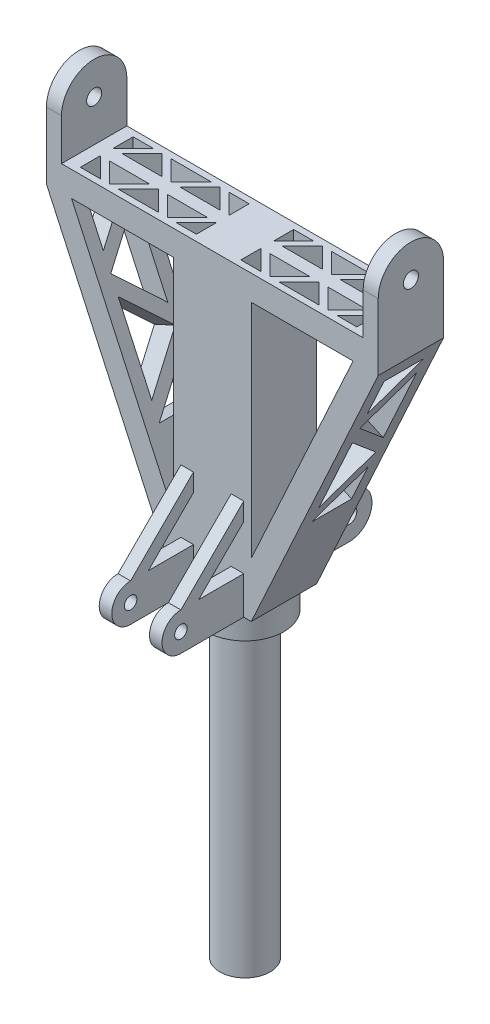
SolidWorks part; units mm, degrees
ref_plane "Front Plane" through (0, 0, 0) normal (0, 0, 1) x (1, 0, 0)
ref_plane "Top Plane" through (0, 0, 0) normal (0, 1, 0) x (1, 0, 0)
ref_plane "Right Plane" through (0, 0, 0) normal (1, 0, 0) x (0, 0, -1)
sketch "Sketch27" plane through (0, 0, 0) normal (0, 0, 1) x (1, 0, 0)
  line L0 (66, -50) -> (-66, -50)
  line L1 (-66, -50) -> (-66, 100)
  line L2 (-66, 100) -> (-60, 100)
  line L3 (-60, 100) -> (-60, 70)
  line L4 (-60, 70) -> (60, 70)
  line L5 (0, 0) -> (0, 82.1741) construction
  line L6 (60, 100) -> (60, 70)
  line L7 (66, 100) -> (60, 100)
  line L8 (66, -50) -> (66, 100)
  point P10 (0, 0)
  point P11 (0, 70)
  dimension "D1" = 120
  dimension "D2" = 6
  dimension "D3" = 150
  dimension "D4" = 30
extrude "Tykkelse leddfester og bredde/høyde selve modellen" add sketch "Sketch27" along normal mid plane 26
sketch "Sketch28" plane through (0, -50, 0) normal (0, -1, 0) x (1, 0, 0)
  line L0 (-66, -13) -> (66, -13) construction
  line L1 (66, 13) -> (66, -13) construction
  circle A1 centre (0, 0) radius 10.5
  circle A2 centre (0, 0) radius 15.5
  point P6 (0, -13)
  point P9 (66, 0)
  dimension "D1" = 21
  dimension "D2" = 5
extrude "Hull til lårben/karbonfiberrør" add sketch "Sketch28" along normal blind 10
sketch "Sketch29" plane through (66, 0, 0) normal (1, 0, 0) x (0, 0, -1)
  line L0 (-13, 100) -> (13, 100) construction
  line L1 (-13, 86.5) -> (-13, 71.5)
  line L2 (13, 86.5) -> (13, 71.5)
  line L4 (-14, 101) -> (0, 101)
  line L8 (0, 86.5) -> (0, 83.5) construction
  line L9 (0, 100) -> (0, 99.5) construction
  line L13 (-13, 71.5) -> (-14, 71.5)
  line L14 (-14, 71.5) -> (-14, 101)
  line L18 (13, 71.5) -> (14, 71.5)
  line L19 (14, 71.5) -> (14, 101)
  line L20 (14, 101) -> (0, 101)
  circle A0 centre (0, 86.5) radius 3
  arc A1 (13, 86.5) -> (-13, 86.5) centre (0, 86.5) ccw
  circle A2 centre (0, 86.5) radius 13 construction
  point P4 (0, 100)
  point P14 (-7, 101)
  dimension "D1" = 6
  dimension "D3" = 15
  dimension "D4" = 0.5
  dimension "D5" = 1
  dimension "D6" = 1
  dimension "D2" = 10
extrude "Skruehull leddfester" cut sketch "Sketch29" against normal through all both and the other way through all
sketch "Fasong (mønster på selve kroppen)" plane through (0, 0, 13) normal (0, 0, 1) x (1, 0, 0)
  line L0 (-66, 60) -> (-15.5, -50)
  line L1 (-66, 86.5) -> (-66, -50) construction
  line L2 (-15.5, -50) -> (-66, -50)
  line L3 (-66, -50) -> (-66, 60)
  line L4 (-60, 70) -> (-66, 70) construction
  line L5 (0, 0) -> (0, 49.2612) construction
  line L6 (15.5, -50) -> (66, -50)
  line L7 (66, 60) -> (15.5, -50)
  line L8 (66, -50) -> (66, 60)
  line L9 (-15.5, -50) -> (-15.5, 60) construction
  line L11 (15.5, -50) -> (15.5, 60) construction
  line L12 (-66, 60) -> (-56, 60) construction
  line L13 (-56, 60) -> (-15.5, -28.2178)
  line L14 (-56, 60) -> (-15.5, 60)
  line L15 (-15.5, 60) -> (-15.5, -28.2178)
  line L16 (56, 60) -> (15.5, 60)
  line L17 (56, 60) -> (15.5, -28.2178)
  line L18 (15.5, 60) -> (15.5, -28.2178)
  dimension "D1" = 10
  dimension "D2" = 10
  dimension "D3" = 31
sketch "Sketch33" plane through (0, 0, -13) normal (0, 0, -1) x (-1, 0, 0)
  line L4 (8.441, -50) -> (-8.441, -50) construction
  line L5 (-3.5, -30) -> (-3.5, -50)
  line L6 (-3.5, -50) -> (-8.5, -50)
  line L7 (-8.5, -50) -> (-8.5, -30)
  line L8 (-8.5, -30) -> (-3.5, -30)
  line L9 (0, 0) -> (0, 33.6157) construction
  line L10 (0, 0) -> (0, 49.2612) construction
  line L11 (8.5, -50) -> (8.5, -30)
  line L12 (3.5, -50) -> (8.5, -50)
  line L13 (3.5, -30) -> (3.5, -50)
  line L14 (8.5, -30) -> (3.5, -30)
  dimension "D1" = 5
  dimension "D2" = 20
  dimension "D3" = 7
extrude "Bredde og avstand stempelende" add sketch "Sketch33" along normal blind 60
sketch "Rod-ende, justere lengden (altså feste til største sylinder)" plane through (8.5, 0, 0) normal (1, 0, 0) x (0, 0, -1)
  line L0 (13, -30) -> (13, -50) construction
  line L5 (43, -51) -> (74, -51)
  line L6 (74, -51) -> (74, -29)
  line L7 (74, -29) -> (43, -29)
  line L9 (73, -50) -> (13, -50) construction
  line L11 (73, -30) -> (73, -50) construction
  line L12 (73, -30) -> (13, -30) construction
  line L13 (33, -49) -> (13, -49)
  line L14 (13, -50) -> (13, 86.5) construction
  line L15 (13, -49) -> (13, -51)
  line L16 (13, -51) -> (43, -51)
  line L17 (43, -29) -> (13, -29)
  line L18 (13, -29) -> (13, -31)
  line L19 (13, -31) -> (33, -31)
  circle A0 centre (33, -40) radius 3
  arc A1 (33, -49) -> (33, -31) centre (33, -40) ccw
  circle A2 centre (33, -40) radius 9 construction
  point P6 (13, -40)
  dimension "D1" = 6
  dimension "D3" = 20
  dimension "D4" = 1
  dimension "D5" = 1
  dimension "D6" = 1
  dimension "D2" = 6
sketch "Sketch39" plane through (0, 0, 13) normal (0, 0, 1) x (1, 0, 0)
  line L1 (-7.5, -50) -> (-7.5, -35)
  line L3 (-7.5, -35) -> (-12.5, -35)
  line L4 (-12.5, -35) -> (-12.5, -50)
  line L5 (-12.5, -50) -> (-7.5, -50)
  line L11 (0, 0) -> (0, 49.2612) construction
  line L12 (0, 0) -> (0, 21.5969) construction
  line L13 (12.5, -50) -> (7.5, -50)
  line L14 (12.5, -35) -> (12.5, -50)
  line L15 (7.5, -35) -> (12.5, -35)
  line L16 (7.5, -50) -> (7.5, -35)
  line L17 (-8.441, -50) -> (8.441, -50) construction
  dimension "D1" = 15
  dimension "D2" = 5
  dimension "D3" = 7.5
extrude "Cut-Extrude4" cut sketch "Fasong (mønster på selve kroppen)" against normal through all
sketch "Sketch40" plane through (-31.7606, -14.581, 0) normal (-0.9088, -0.4172, 0) x (0, 0, 1)
  line L0 (0, 82.065) -> (0, 35.3376) construction
  line L1 (-13, 82.065) -> (13, 82.065) construction
  line L2 (-8, 75.565) -> (8, 75.565)
  line L3 (-13, -38.9732) -> (-13, 82.065) construction
  line L4 (-8, 75.565) -> (8, 59.565)
  line L6 (-8, 68.4939) -> (8, 52.4939)
  line L8 (-8, 36.4939) -> (8, 52.4939)
  line L9 (8, 75.565) -> (8, 59.565)
  line L10 (-8, 36.4939) -> (-8, 68.4939)
  line L13 (8, 13.4229) -> (-8, 29.4229)
  line L16 (8, 45.4229) -> (-8, 29.4229)
  line L18 (8, 13.4229) -> (8, 45.4229)
  line L19 (-8, 22.3518) -> (8, 6.3518)
  line L20 (8, 6.3518) -> (-8, 6.3518)
  line L21 (-8, 6.3518) -> (-8, 22.3518)
  line L22 (-13, -38.9732) -> (0, -38.9732) construction
  point P8 (0, 75.565)
  dimension "D1" = 6.5
  dimension "D2" = 5
  dimension "D3" = 45
  dimension "D4" = 90
  dimension "D5" = 5
  dimension "D6" = 5
  dimension "D7" = 90
  dimension "D8" = 5
  dimension "D9" = 45.325
extrude "Sidemønster" cut sketch "Sketch40" against normal up to vertex (9.088 mm away)
sketch "Sketch42" plane through (31.7606, -14.581, 0) normal (0.9088, -0.4172, 0) x (0, 0, -1)
  line L3 (0, 82.065) -> (0, 75.565) construction
  line L4 (13, 82.065) -> (-13, 82.065) construction
  line L5 (8, 75.565) -> (-8, 75.565)
  line L6 (-13, 82.065) -> (-13, -38.9732) construction
  line L7 (-8, 75.565) -> (-8, 59.565)
  line L8 (-8, 59.565) -> (8, 75.565)
  line L9 (8, 68.4939) -> (-8, 52.4939)
  line L11 (8, 36.4939) -> (8, 68.4939)
  line L12 (8, 36.4939) -> (-8, 52.4939)
  line L13 (-8, 45.4229) -> (8, 29.4229)
  line L15 (-8, 13.4229) -> (-8, 45.4229)
  line L16 (-8, 13.4229) -> (8, 29.4229)
  line L17 (8, 22.3518) -> (-8, 6.3518)
  line L18 (-8, 6.3518) -> (8, 6.3518)
  line L19 (8, 6.3518) -> (8, 22.3518)
  point P8 (0, 82.065)
  point P11 (0, 75.565)
  dimension "D1" = 6.5
  dimension "D2" = 5
  dimension "D3" = 45
  dimension "D4" = 5
  dimension "D5" = 45
  dimension "D6" = 45
  dimension "D7" = 5
  dimension "D9" = 5
extrude "Sidemønster 2" cut sketch "Sketch42" against normal up to vertex (9.088 mm away)
sketch "Sketch44" plane through (0, -50, 0) normal (0, -1, 0) x (1, 0, 0)
  circle A0 centre (0, 0) radius 10.5
  dimension "D1" = 21
extrude "Utvidet lårbenhull inn i selve kroppen" cut sketch "Sketch44" against normal blind 40
sketch "Sketch45" plane through (0, 70, 0) normal (0, 1, 0) x (1, 0, 0)
  line L3 (-39.9289, 10.5) -> (-31.9289, 2.5)
  line L5 (-23.9289, 10.5) -> (-39.9289, 10.5)
  line L6 (-16.8579, 10.5) -> (-8.8579, 2.5)
  line L7 (0, 0) -> (0, 11.265) construction
  line L8 (0, 0) -> (-55, 0) construction
  line L9 (-60, -13) -> (-60, 13) construction
  line L10 (-55, 2.5) -> (-55, 10.5)
  line L11 (-55, 10.5) -> (-47, 10.5)
  line L12 (-47, 10.5) -> (-55, 2.5)
  line L13 (60, 13) -> (-60, 13) construction
  line L14 (-43.4645, 10.5) -> (-51.4645, 2.5)
  line L15 (-51.4645, 2.5) -> (-35.4645, 2.5)
  line L17 (-43.4645, 10.5) -> (-35.4645, 2.5)
  line L18 (-23.9289, 10.5) -> (-31.9289, 2.5)
  line L19 (-20.3934, 10.5) -> (-28.3934, 2.5)
  line L20 (-28.3934, 2.5) -> (-12.3934, 2.5)
  line L22 (-20.3934, 10.5) -> (-12.3934, 2.5)
  line L23 (-8.8579, 2.5) -> (-8.8579, 10.5)
  line L24 (-8.8579, 10.5) -> (-16.8579, 10.5)
  line L25 (-8.8579, -2.5) -> (-8.8579, -10.5)
  line L26 (-16.8579, -10.5) -> (-8.8579, -2.5)
  line L27 (-8.8579, -10.5) -> (-16.8579, -10.5)
  line L28 (-20.3934, -10.5) -> (-12.3934, -2.5)
  line L29 (-28.3934, -2.5) -> (-12.3934, -2.5)
  line L30 (-20.3934, -10.5) -> (-28.3934, -2.5)
  line L31 (-23.9289, -10.5) -> (-31.9289, -2.5)
  line L32 (-23.9289, -10.5) -> (-39.9289, -10.5)
  line L33 (-39.9289, -10.5) -> (-31.9289, -2.5)
  line L34 (-43.4645, -10.5) -> (-35.4645, -2.5)
  line L35 (-51.4645, -2.5) -> (-35.4645, -2.5)
  line L36 (-43.4645, -10.5) -> (-51.4645, -2.5)
  line L37 (-55, -10.5) -> (-47, -10.5)
  line L38 (-55, -2.5) -> (-55, -10.5)
  line L39 (-47, -10.5) -> (-55, -2.5)
  line L40 (8.8579, 2.5) -> (8.8579, 10.5)
  line L41 (16.8579, 10.5) -> (8.8579, 2.5)
  line L42 (8.8579, 10.5) -> (16.8579, 10.5)
  line L43 (16.8579, -10.5) -> (8.8579, -2.5)
  line L44 (8.8579, -10.5) -> (16.8579, -10.5)
  line L45 (8.8579, -2.5) -> (8.8579, -10.5)
  line L46 (20.3934, -10.5) -> (28.3934, -2.5)
  line L47 (28.3934, -2.5) -> (12.3934, -2.5)
  line L48 (20.3934, -10.5) -> (12.3934, -2.5)
  line L49 (20.3934, 10.5) -> (12.3934, 2.5)
  line L50 (28.3934, 2.5) -> (12.3934, 2.5)
  line L51 (20.3934, 10.5) -> (28.3934, 2.5)
  line L52 (23.9289, 10.5) -> (31.9289, 2.5)
  line L53 (23.9289, 10.5) -> (39.9289, 10.5)
  line L54 (39.9289, 10.5) -> (31.9289, 2.5)
  line L55 (23.9289, -10.5) -> (39.9289, -10.5)
  line L56 (39.9289, -10.5) -> (31.9289, -2.5)
  line L57 (23.9289, -10.5) -> (31.9289, -2.5)
  line L58 (43.4645, -10.5) -> (51.4645, -2.5)
  line L59 (51.4645, -2.5) -> (35.4645, -2.5)
  line L60 (43.4645, -10.5) -> (35.4645, -2.5)
  line L61 (55, -2.5) -> (55, -10.5)
  line L62 (47, -10.5) -> (55, -2.5)
  line L63 (55, -10.5) -> (47, -10.5)
  line L64 (43.4645, 10.5) -> (35.4645, 2.5)
  line L65 (51.4645, 2.5) -> (35.4645, 2.5)
  line L66 (43.4645, 10.5) -> (51.4645, 2.5)
  line L67 (55, 10.5) -> (47, 10.5)
  line L68 (55, 2.5) -> (55, 10.5)
  line L69 (47, 10.5) -> (55, 2.5)
  dimension "D1" = 5
  dimension "D2" = 2.5
  dimension "D3" = 2.5
  dimension "D4" = 45
  dimension "D5" = 2.5
  dimension "D6" = 45
  dimension "D7" = 2.5
  dimension "D8" = 45
  dimension "D9" = 2.5
  dimension "D10" = 45
  dimension "D11" = 2.5
extrude "Mønster topp" cut sketch "Sketch45" against normal up to vertex (10 mm away)
extrude "Stempelende av største sylinder " cut sketch "Rod-ende, justere lengden (altså feste til største sylinder)" against normal through all both and the other way through all
extrude "Sylinderfeste, selve den lille sylinderen " add sketch "Sketch39" along normal blind 48
sketch "Sketch46" plane through (8.5, 0, 0) normal (1, 0, 0) x (0, 0, -1)
  line L2 (13, 60) -> (13, -50) construction
  line L3 (13, -14.0039) -> (26.5969, -31)
  line L4 (33, -31) -> (13, -31) construction
  line L5 (26.5969, -31) -> (33, -31)
  line L6 (33, -31) -> (13, -6)
  line L7 (13, -6) -> (13, -14.0039)
  line M3 (33, -31) -> (13, -31)
  dimension "D1" = 5
  dimension "D2" = 25
extrude "Støtter største sylinder 1" add sketch "Sketch46" against normal blind 5 contours L6 L7 L3 M3
sketch "Sketch47" plane through (-8.5, 0, 0) normal (-1, 0, 0) x (0, 0, 1)
  line L0 (-33, -31) -> (-13, -6)
  line L1 (-13, -50) -> (-13, 60) construction
  line L2 (-13, -6) -> (-13, -14.0039) construction
  line L3 (-13, -6) -> (-13, -14.0039)
  line L4 (-13, -14.0039) -> (-26.5969, -31)
  line L5 (-13, -31) -> (-33, -31) construction
  line L6 (-13, -14.0039) -> (-26.5969, -31) construction
  line L7 (-26.5969, -31) -> (-33, -31)
extrude "Støtter største sylinder 2" add sketch "Sketch47" against normal blind 5
sketch "Sketch48" plane through (-12.5, 0, 0) normal (-1, 0, 0) x (0, 0, 1)
  line L0 (13, -35) -> (13, -50) construction
  line L1 (38, -50) -> (23.1798, -50)
  line L2 (23.1798, -50) -> (23.1798, -51)
  line L3 (23.1798, -51) -> (62, -51)
  line L4 (62, -51) -> (62, -34)
  line L5 (62, -34) -> (13, -34)
  line L6 (13, -50) -> (13, 60) construction
  line L7 (13, -34) -> (13, -35)
  line L8 (13, -35) -> (38, -35)
  line L9 (61, -35) -> (13, -35) construction
  line L10 (61, -35) -> (61, -50) construction
  circle A0 centre (38, -42.5) radius 2.5
  arc A1 (38, -50) -> (38, -35) centre (38, -42.5) ccw
  circle A2 centre (38, -42.5) radius 7.5 construction
  point P6 (13, -42.5)
  dimension "D1" = 5
  dimension "D3" = 1
  dimension "D4" = 1
  dimension "D5" = 1
  dimension "D6" = 25
  dimension "D2" = 5
extrude "Sylinderfeste, liten sylinder" cut sketch "Sketch48" against normal through all both and the other way through all
sketch "Sketch49" plane through (-12.5, 0, 0) normal (-1, 0, 0) x (0, 0, 1)
  line L0 (38, -35) -> (13, -10)
  line L1 (13, -50) -> (13, 60) construction
  line L2 (13, -10) -> (13, -17.0711)
  line L3 (30.9289, -35) -> (38, -35)
  line L4 (13, -17.0711) -> (30.9289, -35)
  dimension "D1" = 25
  dimension "D2" = 5
sketch "Sketch50" plane through (12.5, 0, 0) normal (1, 0, 0) x (0, 0, -1)
  line L0 (-38, -35) -> (-30.9289, -35)
  line L1 (-30.9289, -35) -> (-13, -17.0711)
  line L2 (-13, -17.0711) -> (-13, -10)
  line L3 (-13, -10) -> (-38, -35)
extrude "Boss-Extrude11" add sketch "Sketch49" against normal blind 5
extrude "Boss-Extrude12" add sketch "Sketch50" against normal blind 5 contours L3 L0 L1 L2
sketch "Sketch51" plane through (0, -10, 0) normal (0, -1, 0) x (1, 0, 0)
  circle A0 centre (0, 0) radius 10
  dimension "D1" = 20
extrude "TIL ASSEMBLY - SLETT FØR PRINTING" add sketch "Sketch51" along normal blind 170
